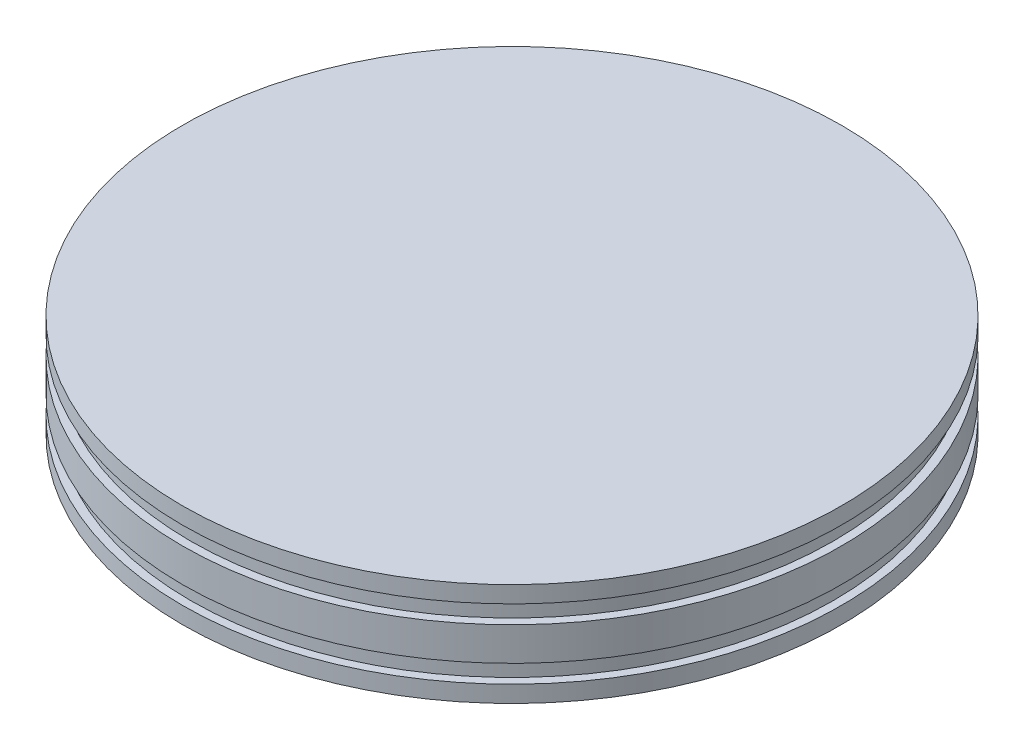
SolidWorks part; units mm, degrees
material "BUTYL"
ref_plane "Front Plane" through (0, 0, 0) normal (0, 0, 1) x (1, 0, 0)
ref_plane "Top Plane" through (0, 0, 0) normal (0, 1, 0) x (1, 0, 0)
ref_plane "Right Plane" through (0, 0, 0) normal (1, 0, 0) x (0, 0, -1)
sketch "Szkic1" plane through (0, 0, 0) normal (0, 1, 0) x (1, 0, 0)
  circle A0 centre (0, 0) radius 64
  dimension "D1" = 128
extrude "Dodanie-wyciągnięcie1" add sketch "Szkic1" along normal blind 20
sketch "Szkic3" plane through (0, 0, 0) normal (1, 0, 0) x (0, 0, -1)
  line L0 (64, 0) -> (-64, 0)
  line L1 (-64, 0) -> (-64, 20)
  line L2 (-64, 20) -> (64, 20)
  line L3 (64, 20) -> (64, 0)
  line L4 (0, 0) -> (0, 50000) construction
  line L5 (-64, 3.25) -> (-62.4, 3.25)
  line L6 (-64, 3.25) -> (-64, 6.75)
  line L7 (-64, 6.75) -> (-62.4, 6.75)
  line L8 (-62.4, 3.25) -> (-62.4, 6.75)
  line L9 (-64, 13.25) -> (-62.4, 13.25)
  line L10 (-64, 13.25) -> (-64, 16.75)
  line L11 (-64, 16.75) -> (-62.4, 16.75)
  line L12 (-62.4, 13.25) -> (-62.4, 16.75)
  dimension "D1" = 1.6
  dimension "D2" = 3.5
  dimension "D3" = 6.5
  dimension "D4" = 3.25
revolve "Wycięcie-obrót1" cut sketch "Szkic3" angle 360 about L4
ref_plane "Płaszczyzna1" through (0, 5, 0) normal (0, 1, 0) x (1, 0, 0)
ref_plane "Płaszczyzna2" through (0, 15, 0) normal (0, 1, 0) x (1, 0, 0)
